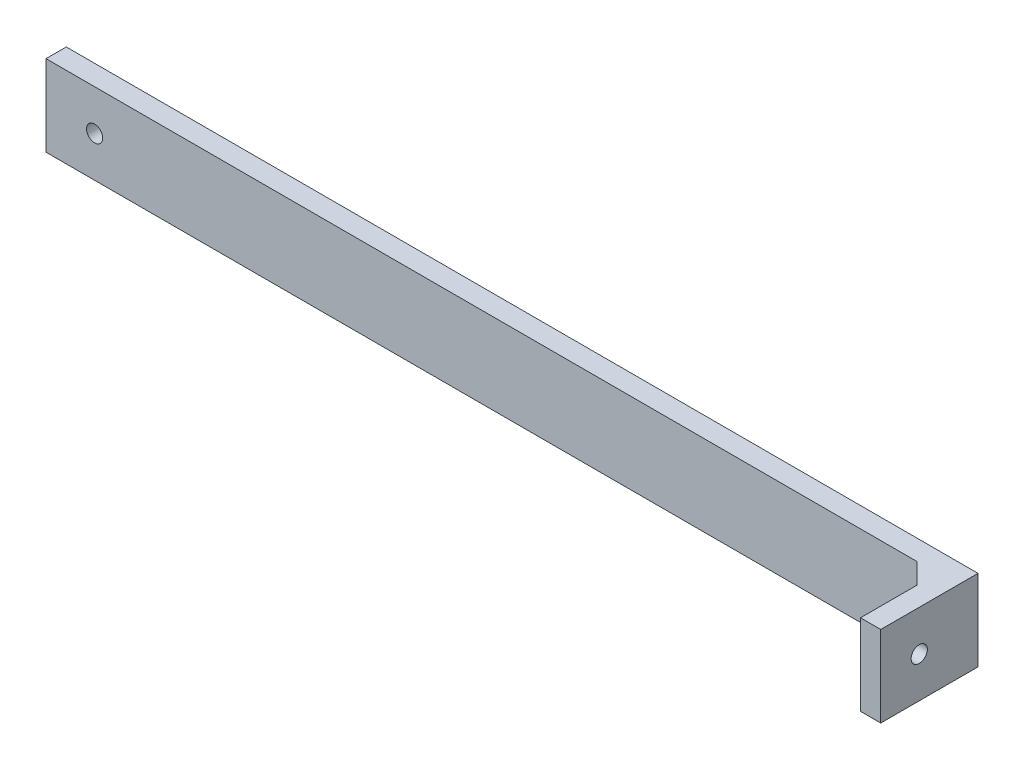
SolidWorks part; units mm, degrees
ref_plane "Front Plane" through (0, 0, 0) normal (0, 0, 1) x (1, 0, 0)
ref_plane "Top Plane" through (0, 0, 0) normal (0, 1, 0) x (1, 0, 0)
ref_plane "Right Plane" through (0, 0, 0) normal (1, 0, 0) x (0, 0, -1)
sketch "Sketch1" plane through (0, 0, 0) normal (0, 0, 1) x (1, 0, 0)
  line L1 (-112.5, -10) -> (112.5, -10)
  line L2 (-112.5, -10) -> (-112.5, 10)
  line L3 (-112.5, 10) -> (112.5, 10)
  line L4 (112.5, -10) -> (112.5, 10)
  line L5 (-112.5, -10) -> (112.5, 10) construction
  line L6 (-112.5, 10) -> (112.5, -10) construction
  point P0 (0, 0)
  dimension "D1" = 20
  dimension "D2" = 225
extrude "Boss-Extrude1" add sketch "Sketch1" along normal blind 5
sketch "Sketch2" plane through (0, 0, 5) normal (0, 0, 1) x (1, 0, 0)
  line L0 (-112.5, -10) -> (112.5, -10) construction
  line L1 (112.5, 10) -> (107.5, 10)
  line L2 (112.5, 10) -> (112.5, -10)
  line L3 (112.5, -10) -> (107.5, -10)
  line L4 (107.5, 10) -> (107.5, -10)
  dimension "D1" = 5
extrude "Boss-Extrude2" add sketch "Sketch2" along normal blind 19
sketch "Sketch3" plane through (112.5, 0, 0) normal (1, 0, 0) x (0, 0, -1)
  line L0 (-24, -10) -> (0, -10) construction
  line L1 (-24, -10) -> (-24, 10) construction
  circle A0 centre (-14.5, 0) radius 2
  dimension "D1" = 4
  dimension "D2" = 10
  dimension "D3" = 9.5
extrude "Cut-Extrude1" cut sketch "Sketch3" against normal through all
sketch "Sketch4" plane through (107.5, 0, 0) normal (-1, 0, 0) x (0, 0, 1)
  line L1 (5, -10) -> (10, -10)
  line L2 (5, -10) -> (5, -5)
  line L3 (5, -5) -> (10, -5)
  line L4 (10, -10) -> (10, -5)
  line L5 (5, 10) -> (10, 10)
  line L6 (5, 10) -> (5, 5)
  line L7 (5, 5) -> (10, 5)
  line L8 (10, 10) -> (10, 5)
  dimension "D1" = 5
  dimension "D2" = 5
  dimension "D3" = 5
  dimension "D4" = 5
extrude "Boss-Extrude3" add sketch "Sketch4" along normal blind 5
sketch "Sketch5" plane through (0, -10, 0) normal (0, -1, 0) x (1, 0, 0)
  line L0 (102.5, 5) -> (107.5, 10)
  line L1 (107.5, 10) -> (102.5, 10)
  line L2 (102.5, 10) -> (102.5, 5)
extrude "Cut-Extrude2" cut sketch "Sketch5" against normal through all
sketch "Sketch6" plane through (0, 0, 0) normal (0, 0, -1) x (-1, 0, 0)
  line L0 (-112.5, -10) -> (-112.5, 10) construction
  line L1 (112.5, -10) -> (-112.5, -10) construction
  circle A0 centre (100.5, 0) radius 2
  dimension "D1" = 4
  dimension "D2" = 213
  dimension "D3" = 10
extrude "Cut-Extrude3" cut sketch "Sketch6" against normal through all
